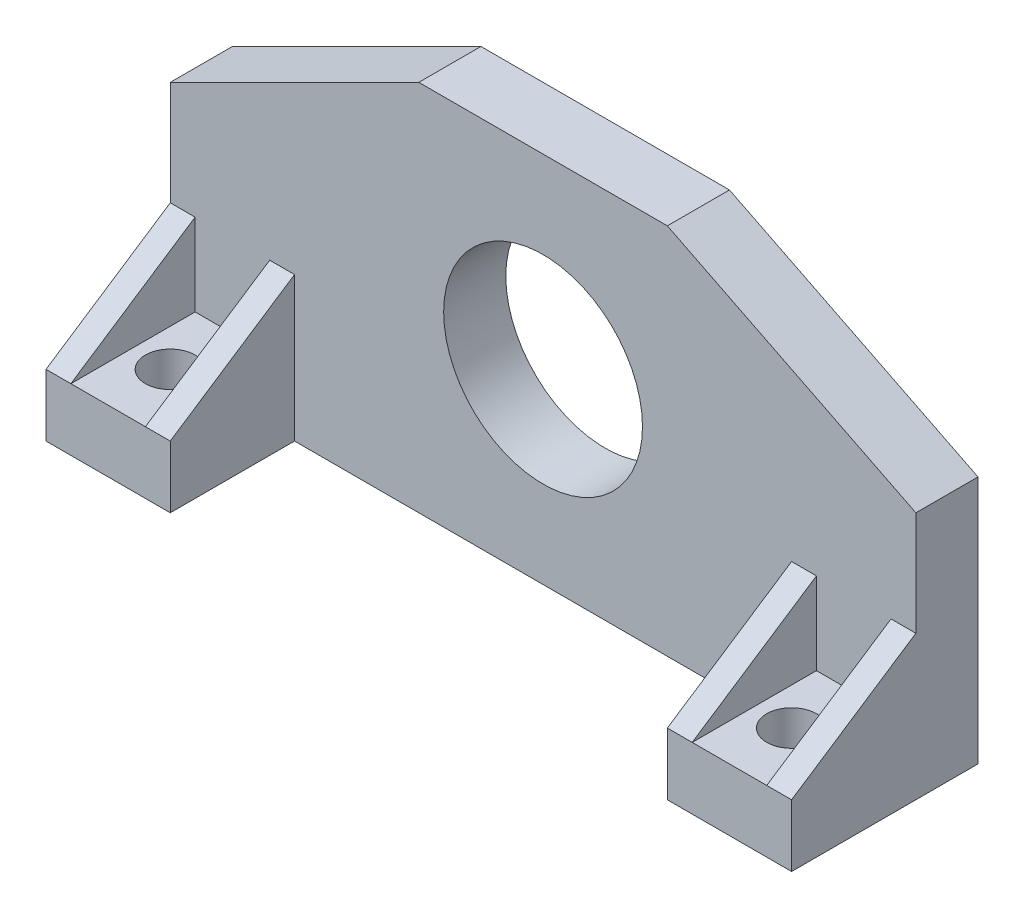
SolidWorks part; units mm, degrees
ref_plane "Plan de face" through (0, 0, 0) normal (0, 0, 1) x (1, 0, 0)
ref_plane "Plan de dessus" through (0, 0, 0) normal (0, 1, 0) x (1, 0, 0)
ref_plane "Plan de droite" through (0, 0, 0) normal (1, 0, 0) x (0, 0, -1)
sketch "Esquisse1" plane through (0, 0, 0) normal (0, 0, 1) x (1, 0, 0)
  line L1 (0, 0) -> (60, 0)
  line L2 (0, 0) -> (0, 30)
  line L3 (0, 30) -> (60, 30)
  line L4 (60, 0) -> (60, 30)
  dimension "D1" = 60
  dimension "D2" = 30
extrude "Boss.-Extru.1" add sketch "Esquisse1" along normal blind 5
sketch "Esquisse2" plane through (0, 0, 5) normal (0, 0, 1) x (1, 0, 0)
  line L0 (0, 0) -> (60, 0) construction
  line L1 (0, 30) -> (0, 0) construction
  circle A0 centre (30, 15) radius 8
  dimension "D1" = 16
  dimension "D2" = 15
  dimension "D3" = 30
extrude "Enlèv. mat.-Extru.1" cut sketch "Esquisse2" against normal blind 5
sketch "Esquisse4" plane through (0, 0, 5) normal (0, 0, 1) x (1, 0, 0)
  line L1 (60, 0) -> (50, 0)
  line L2 (60, 0) -> (60, 5)
  line L3 (60, 5) -> (50, 5)
  line L4 (50, 0) -> (50, 5)
  dimension "D1" = 5
  dimension "D2" = 10
extrude "Boss.-Extru.2" add sketch "Esquisse4" along normal blind 10
ref_plane "Plan1" through (30, 0, 0) normal (1, 0, 0) x (0, 0, -1)
mirror "Symétrie1" about plane through (30, 0, 0) normal (1, 0, 0) of "Boss.-Extru.2"
sketch "Esquisse6" plane through (0, 5, 0) normal (0, 1, 0) x (1, 0, 0)
  line L0 (10, -5) -> (0, -15) construction
  circle A0 centre (5, -10) radius 2
  dimension "D1" = 4
extrude "Enlèv. mat.-Extru.2" cut sketch "Esquisse6" against normal blind 10
mirror "Symétrie2" about plane through (30, 0, 0) normal (1, 0, 0) of "Enlèv. mat.-Extru.2"
ref_plane "Plan2" through (5, 0, 0) normal (-1, 0, 0) x (0, 0, 1)
sketch "Esquisse13" plane through (0, 0, 0) normal (-1, 0, 0) x (0, 0, 1)
  line L0 (15, 5) -> (5, 11.6052)
  line L1 (5, 30) -> (5, 5) construction
  line L2 (5, 11.6052) -> (5, 5)
  line L3 (5, 5) -> (15, 5)
extrude "Boss.-Extru.3" add sketch "Esquisse13" against normal blind 2
mirror "Symétrie3" about plane through (5, 0, 0) normal (-1, 0, 0) of "Boss.-Extru.3"
mirror "Symétrie4" about plane through (30, 0, 0) normal (1, 0, 0) of "Symétrie3", "Boss.-Extru.3"
sketch "Esquisse14" plane through (0, 0, 5) normal (0, 0, 1) x (1, 0, 0)
  line L0 (20, 30) -> (0, 20)
  line L1 (60, 30) -> (0, 30) construction
  line L2 (0, 30) -> (0, 11.6052) construction
  line L3 (0, 20) -> (0, 30)
  line L4 (0, 30) -> (20, 30)
  dimension "D1" = 20
  dimension "D2" = 10
extrude "Enlèv. mat.-Extru.3" cut sketch "Esquisse14" against normal through all
mirror "Symétrie5" about plane through (30, 0, 0) normal (1, 0, 0) of "Enlèv. mat.-Extru.3"
